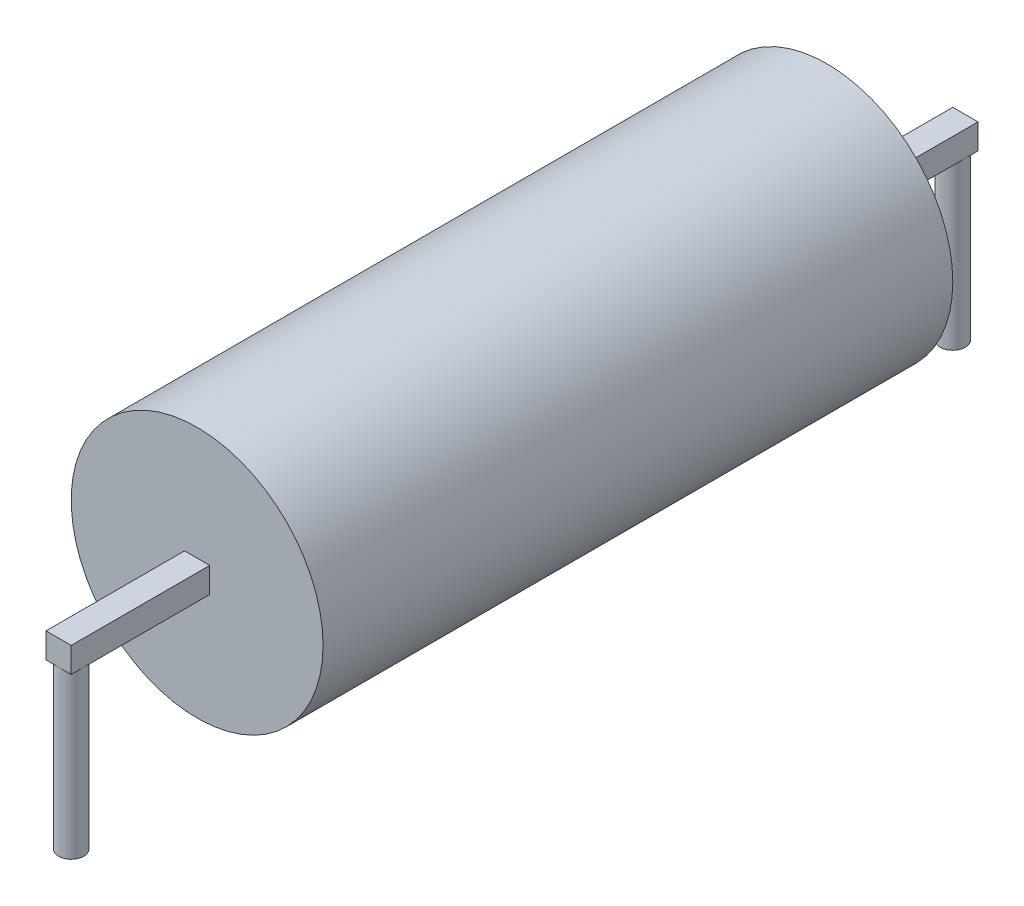
SolidWorks part; units mm, degrees
ref_plane "Спереди" through (0, 0, 0) normal (0, 0, 1) x (1, 0, 0)
ref_plane "Сверху" through (0, 0, 0) normal (0, 1, 0) x (1, 0, 0)
ref_plane "Справа" through (0, 0, 0) normal (1, 0, 0) x (0, 0, -1)
sketch "Эскиз1" plane through (0, 0, 0) normal (0, 0, 1) x (1, 0, 0)
  circle A0 centre (0, 0) radius 5
  dimension "D1" = 10
extrude "Вытянуть1" add sketch "Эскиз1" along normal blind 25
sketch "Эскиз2" plane through (0, 0, 25) normal (0, 0, 1) x (1, 0, 0)
  line L0 (0, 0.6747) -> (0, -0.3959) construction
  line L1 (-0.5, -0.5) -> (0.5, -0.5)
  line L2 (-0.5, -0.5) -> (-0.5, 0.5)
  line L3 (-0.5, 0.5) -> (0.5, 0.5)
  line L4 (0.5, -0.5) -> (0.5, 0.5)
  line L5 (-0.474, 0) -> (0.6636, 0) construction
  dimension "D2" = 1
extrude "Вытянуть2" add sketch "Эскиз2" along normal blind 5.5 and the other way blind 30.5
sketch "Эскиз3" plane through (0, -0.5, 0) normal (0, -1, 0) x (1, 0, 0)
  line L0 (0, 25) -> (0, 0) construction
  line L1 (-0.5, 30.5) -> (0.5, 30.5) construction
  line L2 (-0.5, -5.5) -> (0.5, -5.5) construction
  circle A0 centre (0, 30) radius 0.5
  circle A1 centre (0, -5) radius 0.5
  dimension "D1" = 1
extrude "Вытянуть3" add sketch "Эскиз3" along normal blind 6.5
